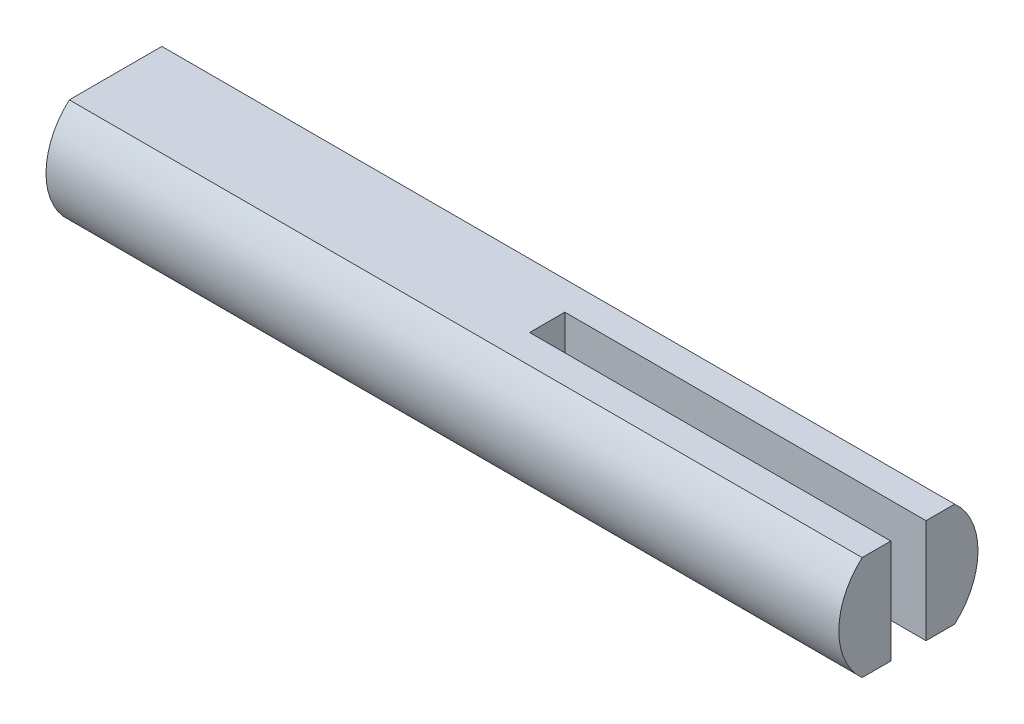
SolidWorks part; units mm, degrees
ref_plane "Front Plane" through (0, 0, 0) normal (0, 0, 1) x (1, 0, 0)
ref_plane "Top Plane" through (0, 0, 0) normal (0, 1, 0) x (1, 0, 0)
ref_plane "Right Plane" through (0, 0, 0) normal (1, 0, 0) x (0, 0, -1)
sketch "Sketch1" plane through (0, 0, 0) normal (1, 0, 0) x (0, 0, -1)
  line L2 (-2.6268, 2.95) -> (2.6268, 2.95)
  line L3 (-2.6268, -2.95) -> (2.6268, -2.95)
  arc A0 (2.6268, -2.95) -> (2.6268, 2.95) centre (0, 0) ccw
  arc A1 (-2.6268, 2.95) -> (-2.6268, -2.95) centre (0, 0) ccw
extrude "Boss-Extrude1" add sketch "Sketch1" along normal blind 40.5 and the other way blind 4.5
sketch "Sketch5" plane through (0, 2.95, 0) normal (0, 1, 0) x (1, 0, 0)
  line L0 (40.5, 0) -> (40.5, 1)
  line L1 (40.5, 2.6268) -> (40.5, -2.6268) construction
  line L2 (40.5, 1) -> (20, 1)
  line L4 (20, -1) -> (40.5, -1)
  line L5 (40.5, -1) -> (40.5, 0)
  line L10 (20, -1) -> (20, 1)
extrude "Cut-Extrude2" cut sketch "Sketch5" against normal through all
